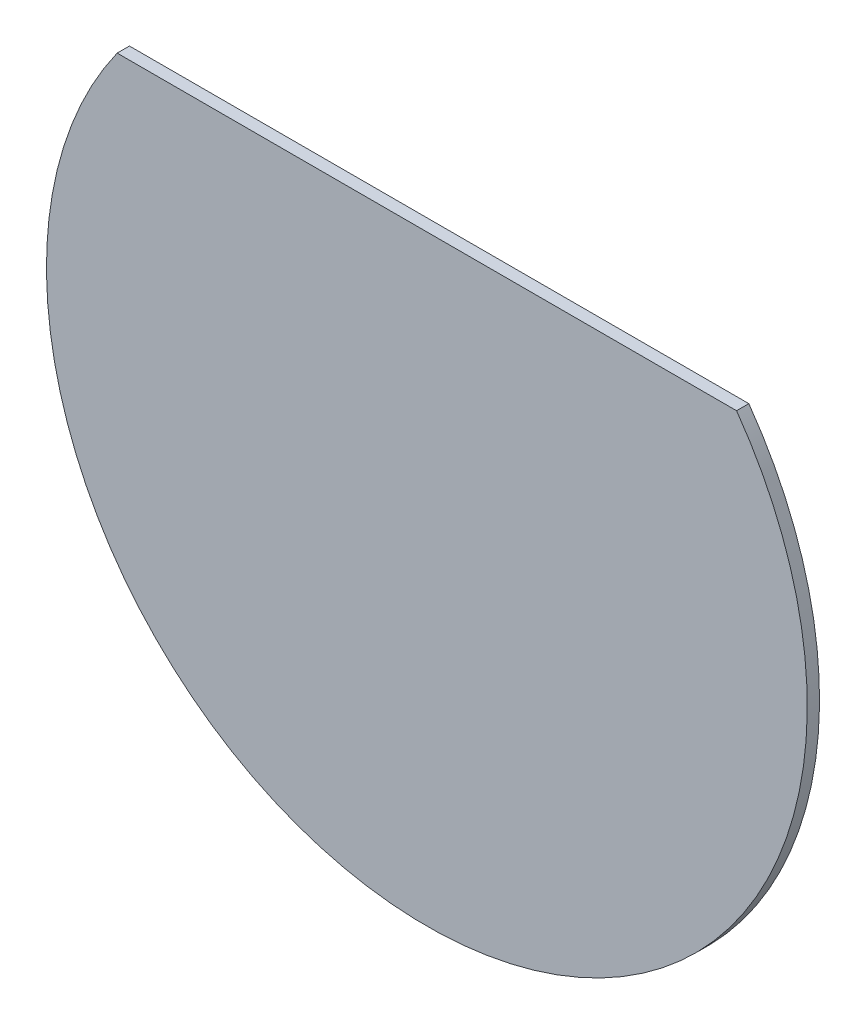
SolidWorks part; units mm, degrees
ref_plane "Front Plane" through (0, 0, 0) normal (0, 0, 1) x (1, 0, 0)
ref_plane "Top Plane" through (0, 0, 0) normal (0, 1, 0) x (1, 0, 0)
ref_plane "Right Plane" through (0, 0, 0) normal (1, 0, 0) x (0, 0, -1)
sketch "Sketch1" plane through (0, 0, 0) normal (0, 0, 1) x (1, 0, 0)
  line L0 (-126.1943, 90) -> (126.1943, 90)
  circle A0 centre (0, 0) radius 135 construction
  arc A1 (-126.1943, 90) -> (126.1943, 90) centre (0, 0) ccw
  circle A2 centre (0, 0) radius 155 construction
  dimension "D3" = 270
  dimension "D2" = 90
  dimension "D1" = 20
extrude "Boss-Extrude1" add sketch "Sketch1" along normal blind 5
